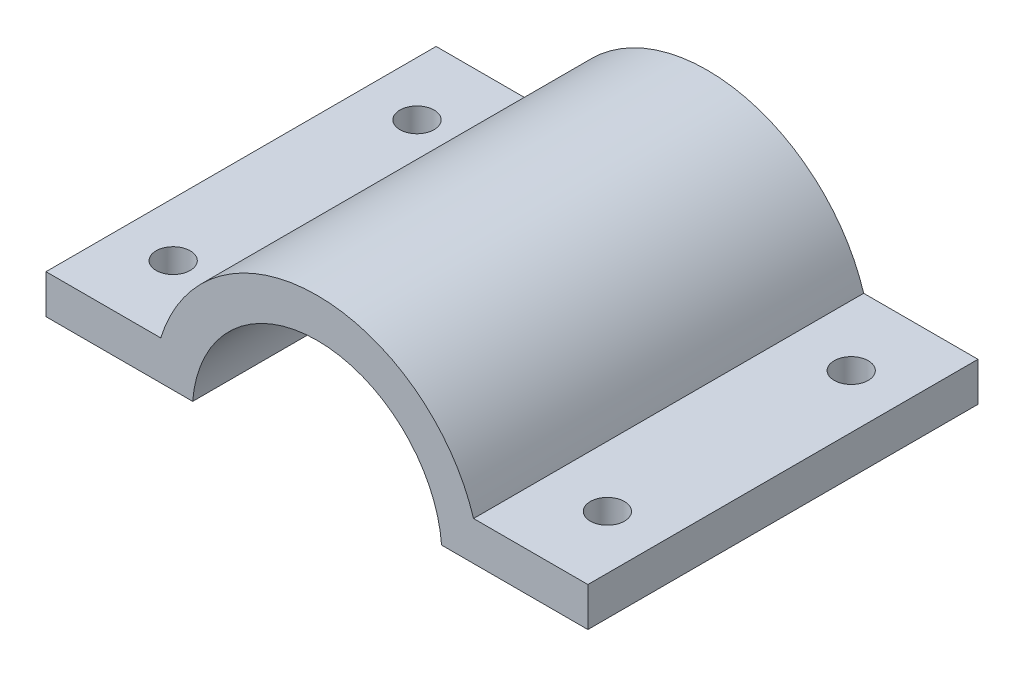
SolidWorks part; units mm, degrees
ref_plane "Front Plane" through (0, 0, 0) normal (1, 0, 0) x (0, 1, 0)
ref_plane "Top Plane" through (0, 0, 0) normal (0, 0, 1) x (0, 1, 0)
ref_plane "Right Plane" through (0, 0, 0) normal (0, 1, 0) x (-1, 0, 0)
sketch "Sketch1" plane through (0, 0, 0) normal (0, 0, 1) x (0, 1, 0)
  line L0 (1, 12.7609) -> (1, 27.8)
  line L1 (1, 27.8) -> (5, 27.8)
  line L2 (5, 27.8) -> (5, 16.0387)
  line L3 (5, -16.0387) -> (5, -27.7609)
  line L4 (5, -27.7609) -> (1, -27.7609)
  line L5 (1, -27.7609) -> (1, -12.7609)
  line L6 (0, 12.8) -> (-12.8, 12.8) construction
  line L7 (-12.8, 12.8) -> (-12.8, 0) construction
  line L8 (-12.8, 0) -> (-12.8, -12.7609) construction
  line L9 (-12.8, -12.7609) -> (1, -12.7609) construction
  circle A0 centre (0, 0) radius 12.8 construction
  arc A1 (5, 16.0387) -> (5, -16.0387) centre (0, 0) cw
  arc A2 (1, -12.7609) -> (1, 12.7609) centre (0, 0) ccw
  dimension "D1" = 25.6
  dimension "D2" = 4
  dimension "D3" = 15
  dimension "D4" = 4
  dimension "D5" = 1
  dimension "D6" = 15
extrude "Boss-Extrude1" add sketch "Sketch1" along normal blind 40
sketch "Sketch2" plane through (0, 5, 0) normal (0, 1, 0) x (-1, 0, 0)
  line L0 (-27.7609, 20) -> (-16.0387, 20) construction
  line L1 (-27.7609, 40) -> (-27.7609, 0) construction
  line L2 (-16.0387, 40) -> (-16.0387, 0) construction
  line L3 (0, 40) -> (0, 0) construction
  line L4 (16.0387, 40) -> (-16.0387, 40) construction
  line L5 (-22.2609, 40) -> (-22.2609, 0) construction
  circle A0 centre (-22.2609, 32.5) radius 1.75
  circle A1 centre (-22.2609, 7.5) radius 1.75
  circle A2 centre (22.2609, 7.5) radius 1.75
  circle A3 centre (22.2609, 32.5) radius 1.75
  dimension "D1" = 3.5
  dimension "D2" = 25
  dimension "D3" = 5.5
extrude "Cut-Extrude1" cut sketch "Sketch2" against normal up to next
